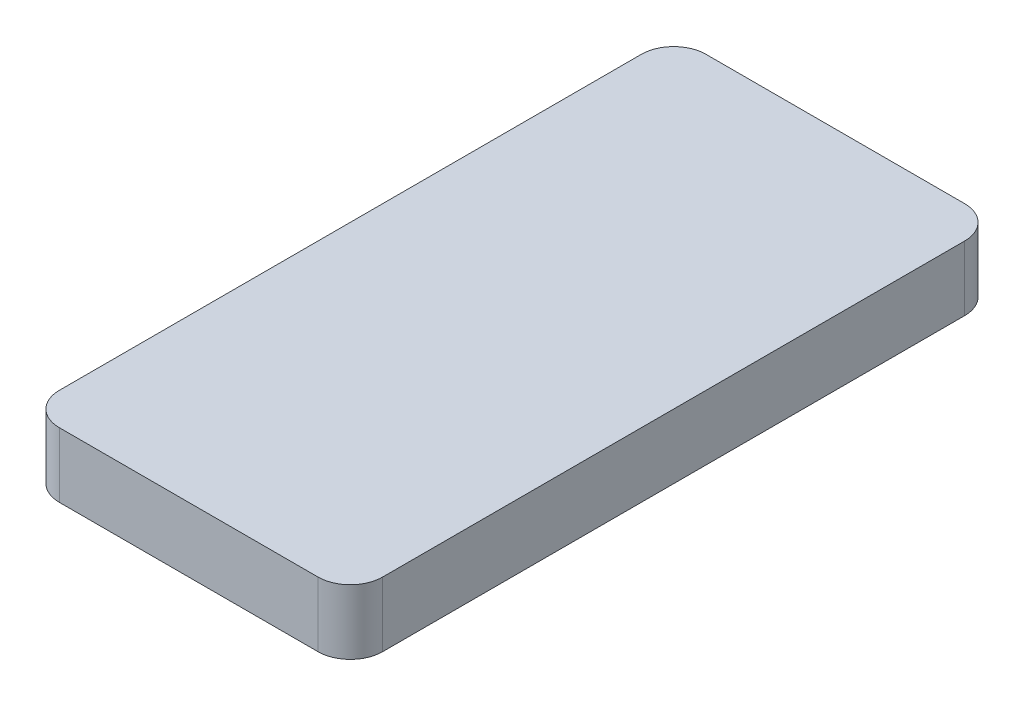
SolidWorks part; units mm, degrees
ref_plane "Front Plane" through (0, 0, 0) normal (0, 0, 1) x (1, 0, 0)
ref_plane "Top Plane" through (0, 0, 0) normal (0, 1, 0) x (1, 0, 0)
ref_plane "Right Plane" through (0, 0, 0) normal (1, 0, 0) x (0, 0, -1)
sketch "Sketch1" plane through (0, 0, 0) normal (0, 1, 0) x (1, 0, 0)
  line L1 (-40, -100) -> (40, -100)
  line L2 (-50, -90) -> (-50, 90)
  line L3 (-40, 100) -> (40, 100)
  line L4 (50, -90) -> (50, 90)
  line L5 (-50, -100) -> (50, 100) construction
  line L6 (-50, 100) -> (50, -100) construction
  arc A0 (40, -100) -> (50, -90) centre (40, -90) ccw
  arc A1 (-40, -100) -> (-50, -90) centre (-40, -90) cw
  arc A2 (-50, 90) -> (-40, 100) centre (-40, 90) cw
  arc A3 (40, 100) -> (50, 90) centre (40, 90) cw
  point P0 (0, 0)
  dimension "D3" = 10
  dimension "D1" = 100
  dimension "D2" = 200
extrude "Boss-Extrude1" add sketch "Sketch1" along normal blind 20
